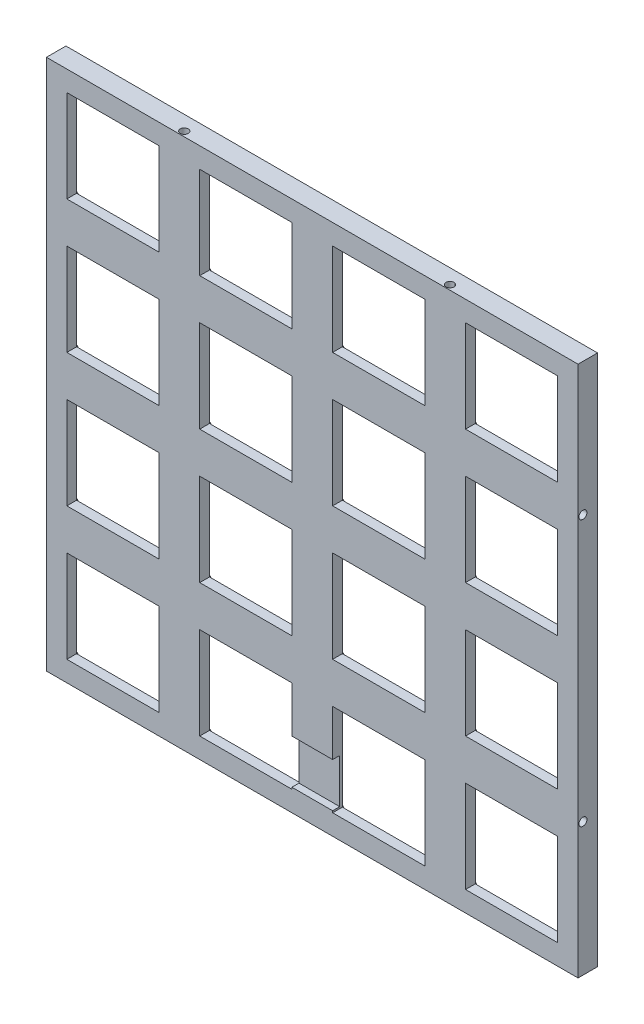
SolidWorks part; units mm, degrees
ref_plane "Front Plane" through (0, 0, 0) normal (0, 0, 1) x (1, 0, 0)
ref_plane "Top Plane" through (0, 0, 0) normal (0, 1, 0) x (1, 0, 0)
ref_plane "Right Plane" through (0, 0, 0) normal (1, 0, 0) x (0, 0, -1)
sketch "Sketch1" plane through (0, 0, 0) normal (0, 0, 1) x (1, 0, 0)
  line L0 (-0.762, 75.438) -> (-0.762, 38.862)
  line L1 (76.2, 76.2) -> (-76.2, 76.2)
  line L2 (76.2, 76.2) -> (76.2, -76.2)
  line L3 (76.2, -76.2) -> (-76.2, -76.2)
  line L4 (-76.2, 76.2) -> (-76.2, -76.2)
  line L5 (76.2, 76.2) -> (-76.2, -76.2) construction
  line L6 (76.2, -76.2) -> (-76.2, 76.2) construction
  line L7 (-75.438, 75.438) -> (-38.862, 75.438)
  line L8 (-75.438, 75.438) -> (-75.438, 38.862)
  line L9 (-75.438, 38.862) -> (-38.862, 38.862)
  line L10 (-38.862, 75.438) -> (-38.862, 38.862)
  line L11 (-37.338, 38.862) -> (-0.762, 38.862)
  line L12 (-37.338, 75.438) -> (-37.338, 38.862)
  line L13 (-37.338, 75.438) -> (-0.762, 75.438)
  line L14 (37.338, 75.438) -> (37.338, 38.862)
  line L15 (0.762, 38.862) -> (37.338, 38.862)
  line L16 (0.762, 75.438) -> (0.762, 38.862)
  line L17 (0.762, 75.438) -> (37.338, 75.438)
  line L18 (75.438, 75.438) -> (75.438, 38.862)
  line L19 (38.862, 38.862) -> (75.438, 38.862)
  line L20 (38.862, 75.438) -> (38.862, 38.862)
  line L21 (38.862, 75.438) -> (75.438, 75.438)
  line L22 (-75.438, 37.338) -> (-75.438, 0.762)
  line L23 (-75.438, 37.338) -> (-38.862, 37.338)
  line L24 (-38.862, 37.338) -> (-38.862, 0.762)
  line L25 (-75.438, 0.762) -> (-38.862, 0.762)
  line L26 (-0.762, 37.338) -> (-0.762, 0.762)
  line L27 (-37.338, 0.762) -> (-0.762, 0.762)
  line L28 (-37.338, 37.338) -> (-37.338, 0.762)
  line L29 (-37.338, 37.338) -> (-0.762, 37.338)
  line L30 (37.338, 37.338) -> (37.338, 0.762)
  line L31 (0.762, 0.762) -> (37.338, 0.762)
  line L32 (0.762, 37.338) -> (0.762, 0.762)
  line L33 (0.762, 37.338) -> (37.338, 37.338)
  line L34 (75.438, 37.338) -> (75.438, 0.762)
  line L35 (38.862, 0.762) -> (75.438, 0.762)
  line L36 (38.862, 37.338) -> (38.862, 0.762)
  line L37 (38.862, 37.338) -> (75.438, 37.338)
  line L38 (-75.438, -0.762) -> (-75.438, -37.338)
  line L39 (-75.438, -0.762) -> (-38.862, -0.762)
  line L40 (-38.862, -0.762) -> (-38.862, -37.338)
  line L41 (-75.438, -37.338) -> (-38.862, -37.338)
  line L42 (-0.762, -0.762) -> (-0.762, -37.338)
  line L43 (-37.338, -37.338) -> (-0.762, -37.338)
  line L44 (-37.338, -0.762) -> (-37.338, -37.338)
  line L45 (-37.338, -0.762) -> (-0.762, -0.762)
  line L46 (37.338, -0.762) -> (37.338, -37.338)
  line L47 (0.762, -37.338) -> (37.338, -37.338)
  line L48 (0.762, -0.762) -> (0.762, -37.338)
  line L49 (0.762, -0.762) -> (37.338, -0.762)
  line L50 (75.438, -0.762) -> (75.438, -37.338)
  line L51 (38.862, -37.338) -> (75.438, -37.338)
  line L52 (38.862, -0.762) -> (38.862, -37.338)
  line L53 (38.862, -0.762) -> (75.438, -0.762)
  line L54 (-75.438, -38.862) -> (-75.438, -75.438)
  line L55 (-75.438, -38.862) -> (-38.862, -38.862)
  line L56 (-38.862, -38.862) -> (-38.862, -75.438)
  line L57 (-75.438, -75.438) -> (-38.862, -75.438)
  line L58 (-0.762, -38.862) -> (-0.762, -75.438)
  line L59 (-37.338, -75.438) -> (-0.762, -75.438)
  line L60 (-37.338, -38.862) -> (-37.338, -75.438)
  line L61 (-37.338, -38.862) -> (-0.762, -38.862)
  line L62 (37.338, -38.862) -> (37.338, -75.438)
  line L63 (0.762, -75.438) -> (37.338, -75.438)
  line L64 (0.762, -38.862) -> (0.762, -75.438)
  line L65 (0.762, -38.862) -> (37.338, -38.862)
  line L66 (75.438, -38.862) -> (75.438, -75.438)
  line L67 (38.862, -75.438) -> (75.438, -75.438)
  line L68 (38.862, -38.862) -> (38.862, -75.438)
  line L69 (38.862, -38.862) -> (75.438, -38.862)
  point P0 (0, 0)
  dimension "D1" = 152.4
  dimension "D2" = 152.4
  dimension "D3" = 36.576
  dimension "D4" = 0.762
  dimension "D7" = 1.524
  dimension "D8" = 1.524
  dimension "D5" = 4
  dimension "D6" = 4
sketch "Sketch2" plane through (0, 0, 0) normal (0, 0, 1) x (1, 0, 0)
  line L1 (76.2, -76.2) -> (-76.2, -76.2)
  line L2 (76.2, -76.2) -> (76.2, 76.2)
  line L3 (76.2, 76.2) -> (-76.2, 76.2)
  line L4 (-76.2, -76.2) -> (-76.2, 76.2)
  line L5 (76.2, -76.2) -> (-76.2, 76.2) construction
  line L6 (76.2, 76.2) -> (-76.2, -76.2) construction
  point P0 (0, 0)
extrude "Boss-Extrude2" add sketch "Sketch2" along normal blind 5.588
sketch "Sketch3" plane through (0, 0, 0) normal (0, 0, -1) x (-1, 0, 0)
  line L1 (-75.438, 75.438) -> (-38.862, 75.438)
  line L2 (-75.438, 75.438) -> (-75.438, 38.862)
  line L3 (-75.438, 38.862) -> (-38.862, 38.862)
  line L4 (-38.862, 75.438) -> (-38.862, 38.862)
  line L5 (-37.338, 75.438) -> (-0.762, 75.438)
  line L6 (-37.338, 75.438) -> (-37.338, 38.862)
  line L7 (-37.338, 38.862) -> (-0.762, 38.862)
  line L8 (-0.762, 75.438) -> (-0.762, 38.862)
  line L9 (-75.438, 37.338) -> (-38.862, 37.338)
  line L10 (-75.438, 37.338) -> (-75.438, 0.762)
  line L11 (-75.438, 0.762) -> (-38.862, 0.762)
  line L12 (-38.862, 37.338) -> (-38.862, 0.762)
  line L13 (-37.338, 37.338) -> (-0.762, 37.338)
  line L14 (-37.338, 37.338) -> (-37.338, 0.762)
  line L15 (-37.338, 0.762) -> (-0.762, 0.762)
  line L16 (-0.762, 37.338) -> (-0.762, 0.762)
  line L17 (0.762, 75.438) -> (37.338, 75.438)
  line L18 (0.762, 75.438) -> (0.762, 38.862)
  line L19 (0.762, 38.862) -> (37.338, 38.862)
  line L20 (37.338, 75.438) -> (37.338, 38.862)
  line L21 (38.862, 75.438) -> (75.438, 75.438)
  line L22 (38.862, 75.438) -> (38.862, 38.862)
  line L23 (38.862, 38.862) -> (75.438, 38.862)
  line L24 (75.438, 75.438) -> (75.438, 38.862)
  line L25 (75.438, 37.338) -> (38.862, 37.338)
  line L26 (75.438, 37.338) -> (75.438, 0.762)
  line L27 (75.438, 0.762) -> (38.862, 0.762)
  line L28 (38.862, 37.338) -> (38.862, 0.762)
  line L29 (37.338, 0.762) -> (0.762, 0.762)
  line L30 (37.338, 0.762) -> (37.338, 37.338)
  line L31 (37.338, 37.338) -> (0.762, 37.338)
  line L32 (0.762, 0.762) -> (0.762, 37.338)
  line L33 (38.862, -0.762) -> (75.438, -0.762)
  line L34 (38.862, -0.762) -> (38.862, -37.338)
  line L35 (38.862, -37.338) -> (75.438, -37.338)
  line L36 (75.438, -0.762) -> (75.438, -37.338)
  line L37 (0.762, -0.762) -> (37.338, -0.762)
  line L38 (0.762, -0.762) -> (0.762, -37.338)
  line L39 (0.762, -37.338) -> (37.338, -37.338)
  line L40 (37.338, -0.762) -> (37.338, -37.338)
  line L41 (-37.338, -0.762) -> (-0.762, -0.762)
  line L42 (-37.338, -0.762) -> (-37.338, -37.338)
  line L43 (-37.338, -37.338) -> (-0.762, -37.338)
  line L44 (-0.762, -0.762) -> (-0.762, -37.338)
  line L45 (-75.438, -0.762) -> (-38.862, -0.762)
  line L46 (-75.438, -0.762) -> (-75.438, -37.338)
  line L47 (-75.438, -37.338) -> (-38.862, -37.338)
  line L48 (-38.862, -0.762) -> (-38.862, -37.338)
  line L49 (-37.338, -38.862) -> (-0.762, -38.862)
  line L50 (-37.338, -38.862) -> (-37.338, -75.438)
  line L51 (-37.338, -75.438) -> (-0.762, -75.438)
  line L52 (-0.762, -38.862) -> (-0.762, -75.438)
  line L53 (-75.438, -38.862) -> (-38.862, -38.862)
  line L54 (-75.438, -38.862) -> (-75.438, -75.438)
  line L55 (-75.438, -75.438) -> (-38.862, -75.438)
  line L56 (-38.862, -38.862) -> (-38.862, -75.438)
  line L57 (0.762, -38.862) -> (37.338, -38.862)
  line L58 (0.762, -38.862) -> (0.762, -75.438)
  line L59 (0.762, -75.438) -> (37.338, -75.438)
  line L60 (37.338, -38.862) -> (37.338, -75.438)
  line L61 (38.862, -38.862) -> (75.438, -38.862)
  line L62 (38.862, -38.862) -> (38.862, -75.438)
  line L63 (38.862, -75.438) -> (75.438, -75.438)
  line L64 (75.438, -38.862) -> (75.438, -75.438)
extrude "Cut-Extrude1" cut sketch "Sketch3" against normal blind 2.794
sketch "Sketch4" plane through (0, 0, 2.794) normal (0, 0, -1) x (-1, 0, 0)
  line L0 (-75.438, -38.862) -> (-75.438, -75.438) construction
  line L1 (-70.358, -43.942) -> (-43.942, -43.942)
  line L2 (-70.358, -43.942) -> (-70.358, -70.358)
  line L3 (-70.358, -70.358) -> (-43.942, -70.358)
  line L4 (-43.942, -43.942) -> (-43.942, -70.358)
  line L5 (-38.862, -38.862) -> (-75.438, -38.862) construction
  line L6 (-75.438, -75.438) -> (-38.862, -75.438) construction
  line L7 (-38.862, -75.438) -> (-38.862, -38.862) construction
  dimension "D1" = 5.08
  dimension "D2" = 5.08
  dimension "D3" = 5.08
  dimension "D4" = 5.08
extrude "Cut-Extrude2" cut sketch "Sketch4" against normal up to next
pattern_linear "LPattern1" count 4 spacing 38.1 along (0, 1, 0) count 4 spacing 38.1 along (-1, 0, 0) of "Cut-Extrude2"
sketch "Sketch5" plane through (0, 0, 2.794) normal (0, 0, -1) x (-1, 0, 0)
  line L0 (75.438, 75.438) -> (38.862, 75.438) construction
  line L1 (38.862, 75.438) -> (38.862, 38.862) construction
  line L2 (41.91, 41.402) -> (41.91, 72.39)
  line L3 (41.91, 72.39) -> (72.898, 72.39)
  circle A0 centre (41.91, 72.39) radius 1.27
  circle A1 centre (41.91, 41.402) radius 1.27
  circle A2 centre (72.898, 72.39) radius 1.27
  circle A3 centre (72.898, 41.402) radius 1.27
  dimension "D3" = 2.54
  dimension "D4" = 2.54
  dimension "D6" = 2.54
  dimension "D8" = 2.54
  dimension "D1" = 3.048
  dimension "D2" = 3.048
  dimension "D5" = 30.988
  dimension "D7" = 30.988
  dimension "D9" = 30.988
  dimension "D10" = 30.988
extrude "Boss-Extrude3" add sketch "Sketch5" along normal blind 2.54
fillet "Fillet1" radius 1.27 4 edges at (-74.168, 72.39, 0.254) (-74.168, 41.402, 0.254) (-43.18, 41.402, 0.254) (-43.18, 72.39, 0.254)
pattern_linear "LPattern2" count 4 spacing 38.1 along (0, -1, 0) count 4 spacing 38.1 along (1, 0, 0) of "Boss-Extrude3", "Fillet1"
sketch "Sketch6" plane through (0, 0, 5.588) normal (0, 0, 1) x (1, 0, 0)
  line L0 (-76.2, -76.2) -> (76.2, -76.2) construction
  line L1 (12.7, -57.15) -> (-12.7, -57.15)
  line L2 (12.7, -57.15) -> (12.7, -69.85)
  line L3 (12.7, -69.85) -> (-12.7, -69.85)
  line L4 (-12.7, -57.15) -> (-12.7, -69.85)
  line L5 (12.7, -57.15) -> (-12.7, -69.85) construction
  line L6 (12.7, -69.85) -> (-12.7, -57.15) construction
  line L7 (0, 76.2) -> (0, -76.2) construction
  line L8 (76.2, 76.2) -> (-76.2, 76.2) construction
  point P0 (0, -63.5)
  dimension "D1" = 12.7
  dimension "D2" = 12.7
  dimension "D3" = 25.4
extrude "Cut-Extrude3" cut sketch "Sketch6" against normal blind 2.032
sketch "Sketch8" plane through (-76.2, 0, 0) normal (-1, 0, 0) x (0, 0, 1)
  line L0 (5.588, 0) -> (0, 0) construction
  line L1 (5.588, 76.2) -> (5.588, -76.2) construction
  line L2 (0, 76.2) -> (0, -76.2) construction
  line L3 (0, -38.1) -> (5.588, -38.1) construction
  line L4 (0, 38.1) -> (5.588, 38.1) construction
  circle A0 centre (4.191, 0) radius 1.143
  circle A1 centre (4.191, -38.1) radius 1.143
  circle A2 centre (4.191, 38.1) radius 1.143
  dimension "D1" = 2.286
  dimension "D4" = 2.286
  dimension "D5" = 2.286
  dimension "D2" = 38.1
  dimension "D3" = 38.1
  dimension "D6" = 1.397
  dimension "D7" = 1.397
  dimension "D8" = 1.397
sketch "Sketch9" plane through (0, -76.2, 0) normal (0, -1, 0) x (1, 0, 0)
  line L0 (-76.2, 5.588) -> (76.2, 5.588) construction
  line L1 (0, 0) -> (0, 5.588) construction
  line L2 (-76.2, 0) -> (76.2, 0) construction
  line L3 (38.1, 0) -> (38.1, 5.588) construction
  line L4 (-38.1, 0) -> (-38.1, 5.588) construction
  circle A0 centre (0, 4.191) radius 1.143
  circle A1 centre (38.1, 4.191) radius 1.143
  circle A2 centre (-38.1, 4.191) radius 1.143
  dimension "D1" = 2.286
  dimension "D2" = 2.286
  dimension "D3" = 2.286
  dimension "D4" = 1.397
  dimension "D5" = 1.397
  dimension "D6" = 1.397
  dimension "D7" = 38.1
  dimension "D8" = 38.1
extrude "Cut-Extrude6" cut sketch "Sketch8" against normal through all contours A1 | A2
extrude "Cut-Extrude7" cut sketch "Sketch9" against normal through all contours A1 | A2
